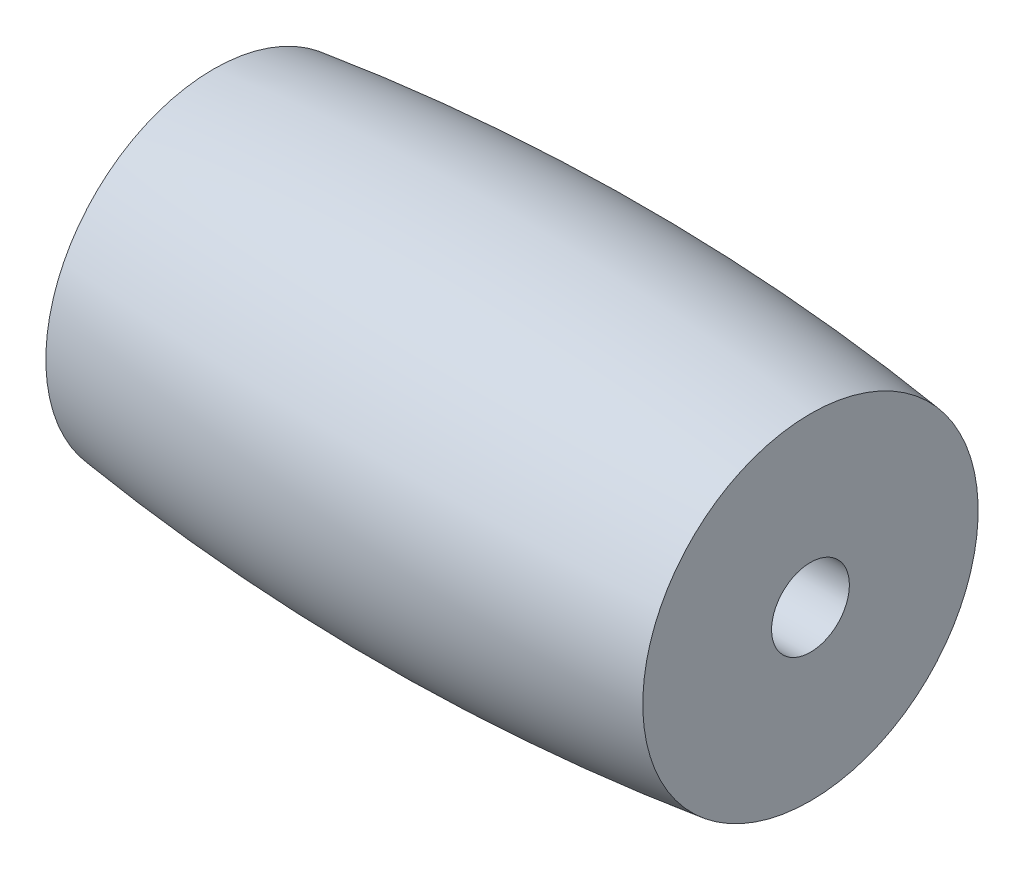
SolidWorks part; units mm, degrees
ref_plane "Front Plane" through (0, 0, 0) normal (0, 0, 1) x (1, 0, 0)
ref_plane "Top Plane" through (0, 0, 0) normal (0, 1, 0) x (1, 0, 0)
ref_plane "Right Plane" through (0, 0, 0) normal (1, 0, 0) x (0, 0, -1)
sketch "Sketch2" plane through (0, 0, 0) normal (0, 0, 1) x (1, 0, 0)
  line L1 (5.6515, 0.7366) -> (5.6515, 3.175)
  line L2 (-5.6515, 0.7366) -> (-5.6515, 3.175)
  line L3 (0, 0) -> (-9.3956, 0) construction
  line L4 (-5.6515, 0.7366) -> (5.6515, 0.7366)
  arc A0 (-5.6515, 3.175) -> (5.6515, 3.175) centre (0, -41.5564) cw
  point P3 (0, 0.7366)
  point P4 (0, 0)
  point P10 (0, 3.5306)
  point P11 (-5.6515, 2.1913)
  point P12 (0, 1.421)
  dimension "D1" = 11.303
  dimension "D2" = 7.0612
  dimension "D3" = 6.35
  dimension "D4" = 1.4732
revolve "Revolve1" add sketch "Sketch2" angle 360 about L3
